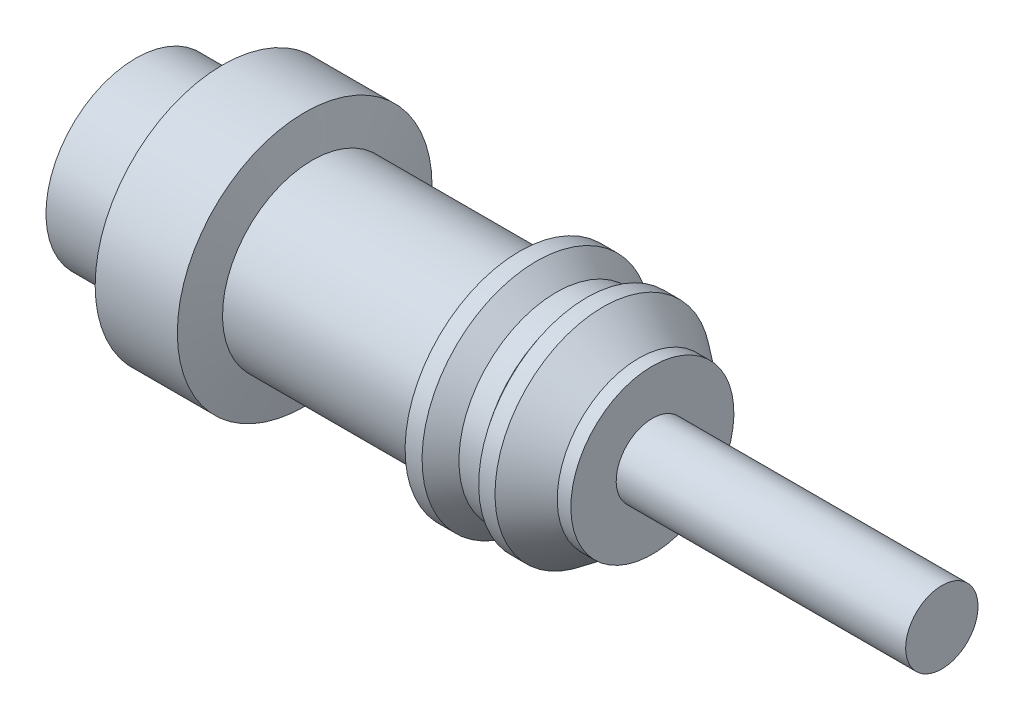
SolidWorks part; units mm, degrees
ref_plane "前视基准面" through (0, 0, 0) normal (0, 0, 1) x (1, 0, 0)
ref_plane "上视基准面" through (0, 0, 0) normal (0, 1, 0) x (1, 0, 0)
ref_plane "右视基准面" through (0, 0, 0) normal (1, 0, 0) x (0, 0, -1)
sketch "草图1" plane through (0, 0, 0) normal (0, 0, 1) x (1, 0, 0)
  line L0 (0, 0) -> (0, 6.2)
  line L1 (0, 6.2) -> (6, 6.2)
  line L2 (6, 6.2) -> (6, 8.8)
  line L3 (6, 8.8) -> (11.6769, 8.8)
  line L4 (11.6769, 8.8) -> (12.2, 6.2)
  line L5 (12.2, 6.2) -> (26.523, 6.2)
  line L6 (26.523, 6.2) -> (26.523, 7.9101)
  line L7 (26.523, 7.9101) -> (27.6958, 7.9101)
  line L8 (27.6958, 7.9101) -> (29.0592, 6.7253)
  line L9 (29.0592, 6.7253) -> (30.6141, 6.7253)
  line L10 (30.6141, 6.7253) -> (31.1695, 7.4707)
  line L11 (31.1695, 7.4707) -> (32.2946, 7.4707)
  line L12 (32.2946, 7.4707) -> (34.7597, 5.6339)
  line L13 (34.7597, 5.6339) -> (35.7, 5.6339)
  line L14 (35.7, 5.6339) -> (35.7, 0)
  line L15 (35.7, 0) -> (0, 0)
  dimension "D1" = 6.2
  dimension "D2" = 35.7
  dimension "D3" = 6
  dimension "D4" = 6.2
  dimension "D5" = 8.8
revolve "旋转1" add sketch "草图1" angle 360 about L15
sketch "草图2" plane through (0, 0, 0) normal (-1, 0, 0) x (0, 0, 1)
  circle A0 centre (0, 0) radius 5.2
  dimension "D1" = 10.4
extrude "切除-拉伸1" cut sketch "草图2" against normal blind 6
sketch "草图3" plane through (35.7, 0, 0) normal (1, 0, 0) x (0, 0, -1)
  circle A0 centre (0, 0) radius 2.5
  dimension "D1" = 5
extrude "凸台-拉伸1" add sketch "草图3" along normal blind 20
